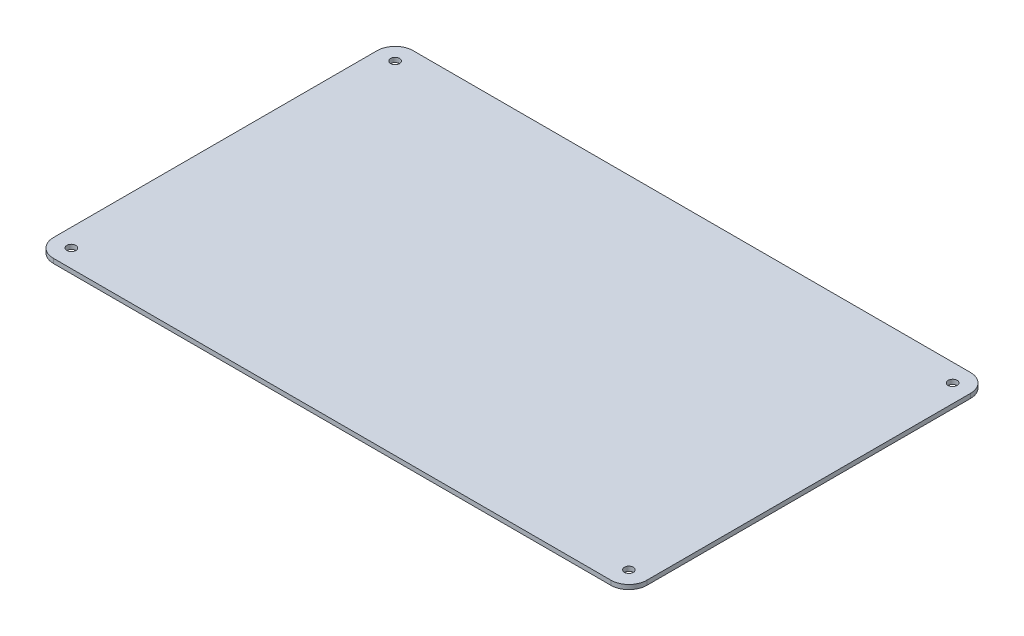
SolidWorks part; units mm, degrees
ref_plane "Front Plane" through (0, 0, 0) normal (0, 0, 1) x (1, 0, 0)
ref_plane "Top Plane" through (0, 0, 0) normal (0, 1, 0) x (1, 0, 0)
ref_plane "Right Plane" through (0, 0, 0) normal (1, 0, 0) x (0, 0, -1)
sketch "Sketch1" plane through (0, 0, 0) normal (0, 1, 0) x (1, 0, 0)
  line L1 (6.35, 0) -> (203.2, 0)
  line L2 (0, 6.35) -> (0, 120.65)
  line L3 (6.35, 127) -> (203.2, 127)
  line L4 (209.55, 6.35) -> (209.55, 120.65)
  circle A0 centre (6.35, 120.65) radius 1.5875
  circle A1 centre (203.2, 120.65) radius 1.5875
  circle A2 centre (203.2, 6.35) radius 1.5875
  circle A3 centre (6.35, 6.35) radius 1.5875
  arc A4 (0, 6.35) -> (6.35, 0) centre (6.35, 6.35) ccw
  arc A5 (203.2, 0) -> (209.55, 6.35) centre (203.2, 6.35) ccw
  arc A6 (209.55, 120.65) -> (203.2, 127) centre (203.2, 120.65) ccw
  arc A7 (6.35, 127) -> (0, 120.65) centre (6.35, 120.65) ccw
  point P15 (0, 0)
  point P20 (209.55, 127)
  point P23 (0, 127)
  dimension "D7" = 3.175
  dimension "D8" = 6.35
  dimension "D1" = 209.55
  dimension "D2" = 127
  dimension "D3" = 114.3
  dimension "D4" = 196.85
  dimension "D5" = 6.35
  dimension "D6" = 6.35
extrude "Boss-Extrude1" add sketch "Sketch1" along normal blind 1.5875
